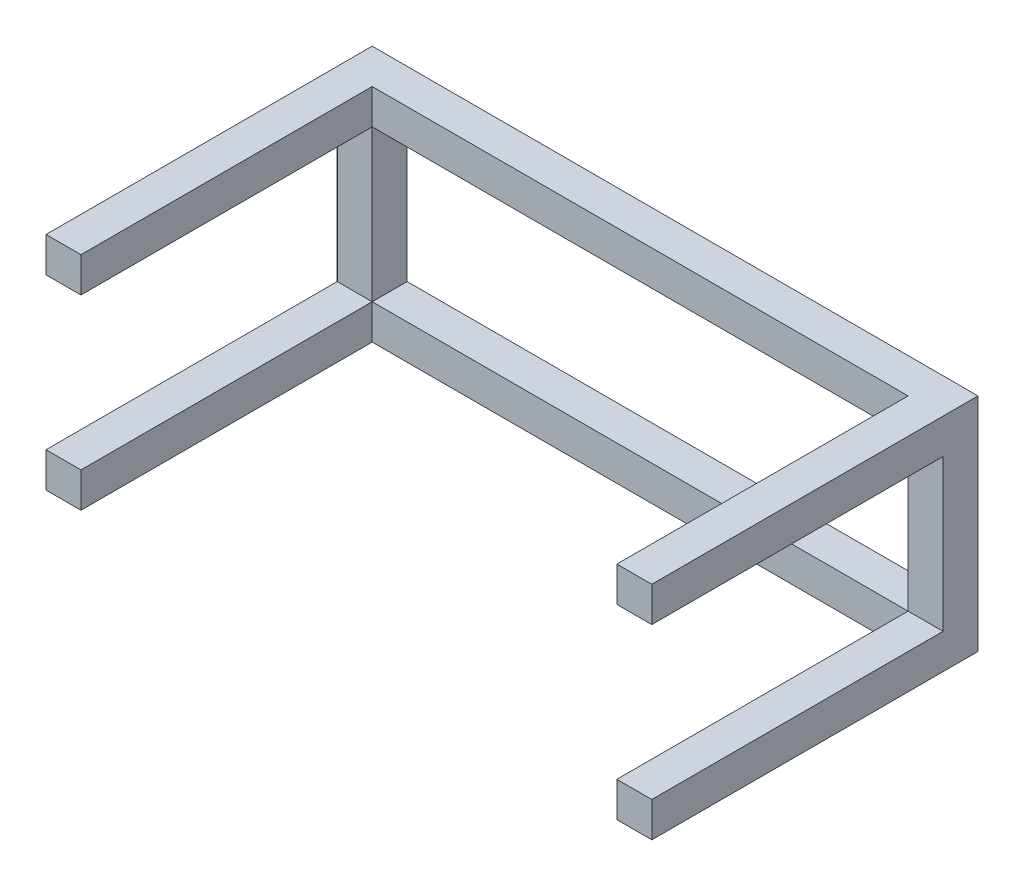
SolidWorks part; units mm, degrees
ref_plane "前视基准面" through (0, 0, 0) normal (0, 0, 1) x (1, 0, 0)
ref_plane "上视基准面" through (0, 0, 0) normal (0, 1, 0) x (1, 0, 0)
ref_plane "右视基准面" through (0, 0, 0) normal (1, 0, 0) x (0, 0, -1)
other "Configuration Table"
sketch "草图1" plane through (0, 0, 0) normal (0, 0, 1) x (1, 0, 0)
  line L1 (0, 0) -> (30, 0)
  line L2 (0, 0) -> (0, 190)
  line L3 (0, 190) -> (30, 190)
  line L4 (30, 0) -> (30, 190)
  line L5 (30, 190) -> (490, 190)
  line L6 (30, 190) -> (30, 160)
  line L7 (30, 160) -> (490, 160)
  line L8 (490, 190) -> (490, 160)
  line L9 (30, 0) -> (490, 0)
  line L10 (30, 0) -> (30, 30)
  line L11 (30, 30) -> (490, 30)
  line L12 (490, 0) -> (490, 30)
  line L13 (490, 190) -> (520, 190)
  line L14 (490, 190) -> (490, 0)
  line L15 (490, 0) -> (520, 0)
  line L16 (520, 190) -> (520, 0)
  dimension "D1" = 190
  dimension "D2" = 30
  dimension "D3" = 460
  dimension "D4" = 30
  dimension "D5" = 30
  dimension "D6" = 30
extrude "凸台-拉伸1" add sketch "草图1" along normal blind 30 contours L1 L4 L3 L2 | L8 L5 L4 L7 | L9 L12 L11 L4 | L16 L13 L8 L14 L12 L15
sketch "草图2" plane through (0, 0, 30) normal (0, 0, 1) x (1, 0, 0)
  line L0 (30, 160) -> (490, 160) construction
  line L1 (0, 190) -> (30, 190)
  line L2 (0, 190) -> (0, 160)
  line L3 (0, 160) -> (30, 160)
  line L4 (30, 190) -> (30, 160)
  line L5 (30, 30) -> (30, 160) construction
  line L7 (30, 30) -> (0, 30)
  line L8 (30, 30) -> (30, 0)
  line L9 (30, 0) -> (0, 0)
  line L10 (0, 30) -> (0, 0)
  line L11 (490, 160) -> (520, 160)
  line L12 (490, 160) -> (490, 190)
  line L13 (490, 190) -> (520, 190)
  line L14 (520, 160) -> (520, 190)
  line L15 (490, 30) -> (520, 30)
  line L16 (490, 30) -> (490, 0)
  line L17 (490, 0) -> (520, 0)
  line L18 (520, 30) -> (520, 0)
extrude "凸台-拉伸2" add sketch "草图2" along normal blind 250
